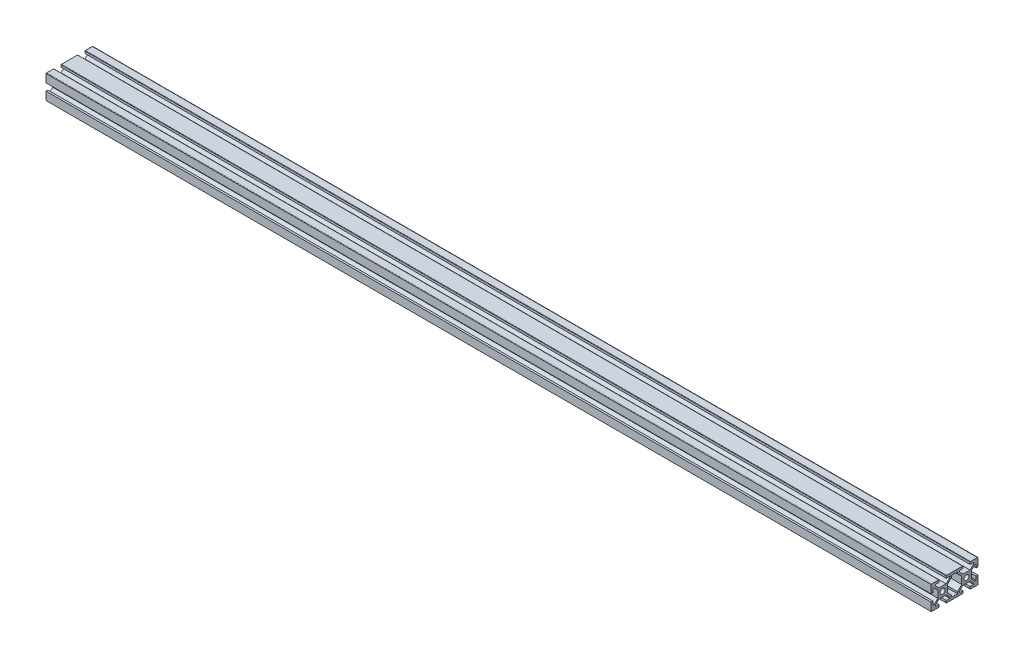
SolidWorks part; units mm, degrees
ref_plane "Front Plane" through (0, 0, 0) normal (0, 0, 1) x (1, 0, 0)
ref_plane "Top Plane" through (0, 0, 0) normal (0, 1, 0) x (1, 0, 0)
ref_plane "Right Plane" through (0, 0, 0) normal (1, 0, 0) x (0, 0, -1)
sketch "Sketch1" plane through (0, 0, 0) normal (0, 0, 1) x (1, 0, 0)
  line L0 (0, 0) -> (740, 0)
  dimension "D1" = 740
other "20xs5 20X40S5(1)"
ref_plane "Plane1" through (0, 0, 0) normal (1, 0, 0) x (0, 1, 0)
sketch "草图11" plane through (0, 0, 0) normal (1, 0, 0) x (0, 1, 0)
  line L0 (-10, 19) -> (-10, 13.3)
  line L1 (-9.7, 13) -> (-8, 13)
  line L2 (-8, 13) -> (-8, 16)
  line L3 (-8, 16) -> (-7.0607, 16)
  line L4 (-7.0607, 16) -> (-4, 12.9393)
  line L5 (-4, 12.9393) -> (-4, 7.0607)
  line L6 (-4, 7.0607) -> (-7.0607, 4)
  line L7 (-7.0607, 4) -> (-8, 4)
  line L8 (-8, 4) -> (-8, 7)
  line L9 (-8, 7) -> (-9.7, 7)
  line L10 (-10, 6.7) -> (-10, -6.7)
  line L11 (-9.7, -7) -> (-8, -7)
  line L12 (-8, -7) -> (-8, -4)
  line L13 (-8, -4) -> (-7.0607, -4)
  line L14 (-7.0607, -4) -> (-4, -7.0607)
  line L15 (-4, -7.0607) -> (-4, -12.9393)
  line L16 (-4, -12.9393) -> (-7.0607, -16)
  line L17 (-7.0607, -16) -> (-8, -16)
  line L18 (-8, -16) -> (-8, -13)
  line L19 (-8, -13) -> (-9.7, -13)
  line L20 (-10, -13.3) -> (-10, -19)
  line L21 (-9.8, -19.6) -> (-3, -19.6)
  line L22 (-3, -19.6) -> (-3, -18)
  line L23 (-3, -18) -> (-6, -18)
  line L24 (-6, -18) -> (-6, -17.0607)
  line L25 (-6, -17.0607) -> (-2.9393, -14)
  line L26 (-2.9393, -14) -> (2.9393, -14)
  line L27 (2.9393, -14) -> (6, -17.0607)
  line L28 (6, -17.0607) -> (6, -18)
  line L29 (6, -18) -> (3, -18)
  line L30 (3, -18) -> (3, -19.6)
  line L31 (3, -19.6) -> (9.8, -19.6)
  line L32 (10, -19) -> (10, -13.3)
  line L33 (9.7, -13) -> (8, -13)
  line L34 (8, -13) -> (8, -16)
  line L35 (8, -16) -> (7.0607, -16)
  line L36 (7.0607, -16) -> (4, -12.9393)
  line L37 (4, -12.9393) -> (4, -7.0607)
  line L38 (4, -7.0607) -> (7.0607, -4)
  line L39 (7.0607, -4) -> (8, -4)
  line L40 (8, -4) -> (8, -7)
  line L41 (8, -7) -> (9.7, -7)
  line L42 (10, -6.7) -> (10, 6.7)
  line L43 (9.7, 7) -> (8, 7)
  line L44 (8, 7) -> (8, 4)
  line L45 (8, 4) -> (7.0607, 4)
  line L46 (7.0607, 4) -> (4, 7.0607)
  line L47 (4, 7.0607) -> (4, 12.9393)
  line L48 (4, 12.9393) -> (7.0607, 16)
  line L49 (7.0607, 16) -> (8, 16)
  line L50 (8, 16) -> (8, 13)
  line L51 (8, 13) -> (9.7, 13)
  line L52 (10, 13.3) -> (10, 19)
  line L53 (9.8, 19.6) -> (3, 19.6)
  line L54 (3, 19.6) -> (3, 18)
  line L55 (3, 18) -> (6, 18)
  line L56 (6, 18) -> (6, 17.0607)
  line L57 (6, 17.0607) -> (2.9393, 14)
  line L58 (2.9393, 14) -> (-2.9393, 14)
  line L59 (-2.9393, 14) -> (-6, 17.0607)
  line L60 (-6, 17.0607) -> (-6, 18)
  line L61 (-6, 18) -> (-3, 18)
  line L62 (-3, 18) -> (-3, 19.6)
  line L63 (-3, 19.6) -> (-9.8, 19.6)
  line L64 (-8, -2.5) -> (-6.4393, -2.5)
  line L65 (-6.4393, -2.5) -> (-2.9393, -6)
  line L66 (-2.9393, -6) -> (2.9393, -6)
  line L67 (2.9393, -6) -> (6.4393, -2.5)
  line L68 (6.4393, -2.5) -> (8, -2.5)
  line L69 (8, -2.5) -> (8, 2.5)
  line L70 (8, 2.5) -> (6.4393, 2.5)
  line L71 (6.4393, 2.5) -> (2.9393, 6)
  line L72 (2.9393, 6) -> (-2.9393, 6)
  line L73 (-2.9393, 6) -> (-6.4393, 2.5)
  line L74 (-6.4393, 2.5) -> (-8, 2.5)
  line L75 (-8, 2.5) -> (-8, -2.5)
  arc A0 (-10, 13.3) -> (-9.7, 13) centre (-9.7, 13.3) ccw
  arc A1 (-9.7, 7) -> (-10, 6.7) centre (-9.7, 6.7) ccw
  arc A2 (-10, -6.7) -> (-9.7, -7) centre (-9.7, -6.7) ccw
  arc A3 (-9.7, -13) -> (-10, -13.3) centre (-9.7, -13.3) ccw
  arc A4 (-10, -19) -> (-9.8, -19.6) centre (-9, -19) ccw
  arc A5 (9.8, -19.6) -> (10, -19) centre (9, -19) ccw
  arc A6 (10, -13.3) -> (9.7, -13) centre (9.7, -13.3) ccw
  arc A7 (9.7, -7) -> (10, -6.7) centre (9.7, -6.7) ccw
  arc A8 (10, 6.7) -> (9.7, 7) centre (9.7, 6.7) ccw
  arc A9 (9.7, 13) -> (10, 13.3) centre (9.7, 13.3) ccw
  arc A10 (10, 19) -> (9.8, 19.6) centre (9, 19) ccw
  arc A11 (-9.8, 19.6) -> (-10, 19) centre (-9, 19) ccw
  circle A12 centre (0, -10) radius 2.1
  circle A13 centre (0, 10) radius 2.1
  point P104 (-10, 19.6)
  point P105 (0, 19.6)
  point P106 (10, 19.6)
  point P107 (10, 10)
  point P108 (10, -10)
  point P109 (10, -19.6)
  point P110 (0, -19.6)
  point P111 (-10, -19.6)
  point P112 (-10, -10)
  point P113 (-10, 10)
  point P114 (-10, 0)
  point P115 (10, 0)
  point P116 (0, 0)
